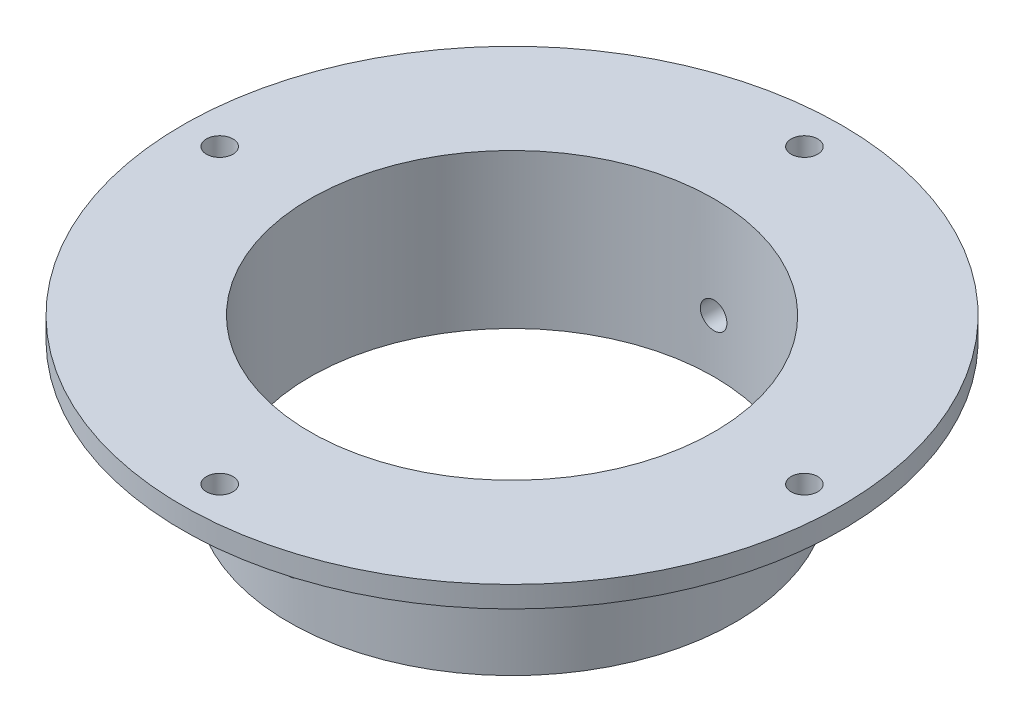
SolidWorks part; units mm, degrees
ref_plane "Front Plane" through (0, 0, 0) normal (0, 0, 1) x (1, 0, 0)
ref_plane "Top Plane" through (0, 0, 0) normal (0, 1, 0) x (1, 0, 0)
ref_plane "Right Plane" through (0, 0, 0) normal (1, 0, 0) x (0, 0, -1)
sketch "Sketch1" plane through (0, 0, 0) normal (0, 0, 1) x (1, 0, 0)
  line L0 (-42, -29) -> (-42, -4)
  line L25 (-42, -4) -> (-62, -4)
  line L26 (-62, -4) -> (-62, 0)
  line L31 (-62, 0) -> (-38, 0)
  line L36 (-38, 0) -> (-38, -29)
  line L37 (-38, -29) -> (-42, -29)
  point P0 (0, 0)
  point P1 (0, 0)
  dimension "D3" = 4
  dimension "D6" = 4
  dimension "D9" = 38
  dimension "D10" = 25
  dimension "D13" = 20
ref_axis "Axis1" through (0, -100.5, 0) along (0, 1, 0)
revolve "Revolve1" add sketch "Sketch1" angle 360 about axis through (0, -100.5, 0) along (0, 1, 0)
sketch "Sketch2" plane through (0, -4, 0) normal (0, -1, 0) x (1, 0, 0)
  circle A0 centre (55, 0) radius 2.5
  circle A1 centre (-55, 0) radius 2.5
  circle A2 centre (0, 0) radius 62 construction
  circle A3 centre (0, 55) radius 2.5
  circle A4 centre (0, -55) radius 2.5
  dimension "D1" = 5
  dimension "D3" = 55
  dimension "D2" = 55
  dimension "D4" = 55
  dimension "D5" = 55
extrude "Cut-Extrude3" cut sketch "Sketch2" against normal through all
sketch "Sketch6" plane through (0, 0, 0) normal (0, 0, 1) x (1, 0, 0)
  line L0 (0, -100.5) -> (0, 20.5) construction
  line L1 (-42, -29) -> (42, -29) construction
  circle A0 centre (0, -19) radius 2.5
  dimension "D1" = 5
  dimension "D2" = 10
extrude "Cut-Extrude6" cut sketch "Sketch6" against normal through all both and the other way through all
